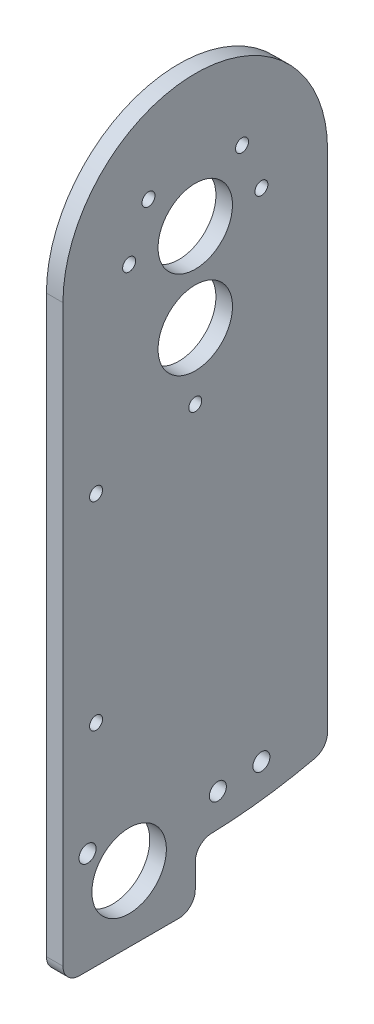
SolidWorks part; units mm, degrees
ref_plane "Front Plane" through (0, 0, 0) normal (1, 0, 0) x (0, 1, 0)
ref_plane "Top Plane" through (0, 0, 0) normal (0, 0, 1) x (0, 1, 0)
ref_plane "Right Plane" through (0, 0, 0) normal (0, 1, 0) x (-1, 0, 0)
sketch "Sketch1" plane through (0, 0, 0) normal (1, 0, 0) x (0, 1, 0)
  line L0 (0, -50.8) -> (-198.7144, -50.8)
  line L1 (0, 0) -> (-205.105, 0) construction
  line L2 (0, 0) -> (0, 50.8) construction
  line L3 (0, 0) -> (-205.105, 0) construction
  line L4 (0, 50.8) -> (-198.7144, 50.8)
  circle A0 centre (0, 0) radius 50.8 construction
  arc A1 (-198.7144, 50.8) -> (-198.7144, -50.8) centre (0, 0) ccw
  arc A2 (0, 50.8) -> (0, -50.8) centre (0, 0) cw
  arc A3 (-175.6828, 50.8) -> (-175.6828, -50.8) centre (0, 0) ccw construction
  arc A4 (-178.9855, 50.8) -> (-178.9855, -50.8) centre (0, 0) ccw construction
  circle A6 centre (0, 0) radius 14.2875
  circle A7 centre (-33.782, 0) radius 14.2875
  point P24 (0, 0)
  dimension "D1" = 101.6
  dimension "D2" = 0
  dimension "D3" = 132.08
  dimension "D4" = 3.175
  dimension "D5" = 19.05
  dimension "D6" = 33.782
  dimension "D7" = 28.575
extrude "Boss-Extrude1" add sketch "Sketch1" along normal blind 6.35
sketch "Sketch4" plane through (6.35, 0, 0) normal (1, 0, 0) x (0, 1, 0)
  line L0 (-198.7144, -50.8) -> (0, -50.8) construction
  circle A0 centre (0, 0) radius 192.405 construction
  arc A1 (-198.7144, 50.8) -> (-198.7144, -50.8) centre (0, 0) ccw construction
  point P6 (-190.7211, -25.4)
  point P7 (-192.2091, -8.6809)
  point P10 (-187.9065, 41.3623)
  point P12 (0, 0)
  dimension "D1" = 12.7
  dimension "D3" = 25.4
  dimension "D4" = 5
  dimension "D2" = 15
hole_wizard "F (0.257) Diameter Hole1" positions "Sketch4" profile "Sketch5" hole size "F" standard "ANSI Inch" end condition through all
sketch "Sketch5" plane through (6.35, 0, 0) normal (0, 1, 0) x (0, 0, -1)
  line L0 (0, 0) -> (0, 6.35)
  line L1 (0, 6.35) -> (3.2639, 6.35)
  line L2 (3.2639, 6.35) -> (3.2639, 0)
  line L5 (3.2639, 0) -> (0, 0)
  line L11 (0, -6.35) -> (0, 107.95) construction
  dimension "Thru Hole Dia." = 6.5278
  dimension "Thru Hole Depth" = 6.35
sketch "Sketch6" plane through (6.35, 0, 0) normal (1, 0, 0) x (0, 1, 0)
  line L0 (0, 50.8) -> (-198.7144, 50.8) construction
  point P0 (-146.05, 38.1)
  point P1 (-69.85, 38.1)
  dimension "D1" = 76.2
  dimension "D2" = 69.85
  dimension "D3" = 12.7
hole_wizard "#9 (0.196) Diameter Hole1" positions "Sketch6" profile "Sketch7" hole size "#9" standard "ANSI Inch" end condition through all
sketch "Sketch7" plane through (6.35, -146.05, 38.1) normal (0, 1, 0) x (0, 0, -1)
  line L0 (0, 0) -> (0, 6.35)
  line L1 (0, 6.35) -> (2.4892, 6.35)
  line L2 (2.4892, 6.35) -> (2.4892, 0)
  line L5 (2.4892, 0) -> (0, 0)
  line L11 (0, -6.35) -> (0, 107.95) construction
  dimension "Thru Hole Dia." = 4.9784
  dimension "Thru Hole Depth" = 6.35
sketch "Sketch8" plane through (0, 0, 0) normal (-1, 0, 0) x (0, -1, 0)
  circle A0 centre (0, 0) radius 25.4 construction
  circle A1 centre (33.782, 0) radius 14.2875 construction
  point P3 (0, 25.4)
  point P4 (0, -25.4)
  point P5 (-17.9605, -17.9605)
  point P6 (-17.9605, 17.9605)
  point P8 (59.182, 0)
  dimension "D1" = 50.8
  dimension "D4" = 25.4
  dimension "D2" = 45
  dimension "D3" = 45
hole_wizard "#9 (0.196) Diameter Hole2" positions "Sketch8" profile "Sketch9" hole size "#9" standard "ANSI Inch" end condition through all
sketch "Sketch9" plane through (0, -59.182, 0) normal (0, 1, 0) x (0, 0, 1)
  line L0 (0, 0) -> (0, 6.35)
  line L1 (0, 6.35) -> (2.4892, 6.35)
  line L2 (2.4892, 6.35) -> (2.4892, 0)
  line L5 (2.4892, 0) -> (0, 0)
  line L11 (0, -6.35) -> (0, 107.95) construction
  dimension "Thru Hole Dia." = 4.9784
  dimension "Thru Hole Depth" = 6.35
sketch "Sketch10" plane through (6.35, 0, 0) normal (1, 0, 0) x (0, 1, 0)
  line L0 (0, 50.8) -> (-198.7144, 50.8) construction
  line L1 (-198.7144, 50.8) -> (-227.0062, 50.8)
  line L2 (-198.7144, 50.8) -> (-198.7144, 0) construction
  line L3 (-198.7144, 0) -> (-227.0062, 0) construction
  line L4 (-227.0062, 50.8) -> (-227.0062, 0)
  line L5 (-227.0062, 0) -> (-205.105, 0)
  line L6 (-201.2296, 39.6825) -> (-198.7144, 50.8)
  circle A0 centre (0, 0) radius 50.8 construction
  circle A1 centre (0, 0) radius 50.8 construction
  circle A2 centre (-201.6062, 25.4) radius 25.4 construction
  arc A3 (-198.7144, 50.8) -> (-198.7144, -50.8) centre (0, 0) ccw construction
  circle A4 centre (-201.6062, 25.4) radius 14.2875 construction
  arc A5 (-198.7144, 50.8) -> (-198.7144, -50.8) centre (0, 0) ccw construction
  arc A7 (-205.105, 0) -> (-204.784, 11.4704) centre (0, 0) cw
  arc A8 (-204.784, 11.4704) -> (-201.2296, 39.6825) centre (-201.6062, 25.4) cw
  dimension "D1" = 50.8
  dimension "D2" = 127
  dimension "D3" = 28.575
extrude "Boss-Extrude3" add sketch "Sketch10" against normal blind 6.35
sketch "Sketch11" plane through (6.35, 0, 0) normal (1, 0, 0) x (0, 1, 0)
  circle A0 centre (-201.6062, 25.4) radius 14.2875 construction
  circle A1 centre (-201.6062, 25.4) radius 14.2875
extrude "Cut-Extrude1" cut sketch "Sketch11" against normal blind 6.35
fillet "Fillet1" radius 6.35 4 edges at (3.175, -198.7144, -50.8) (3.175, -205.105, 0) (3.175, -227.0062, 0) (3.175, -227.0062, 50.8)
